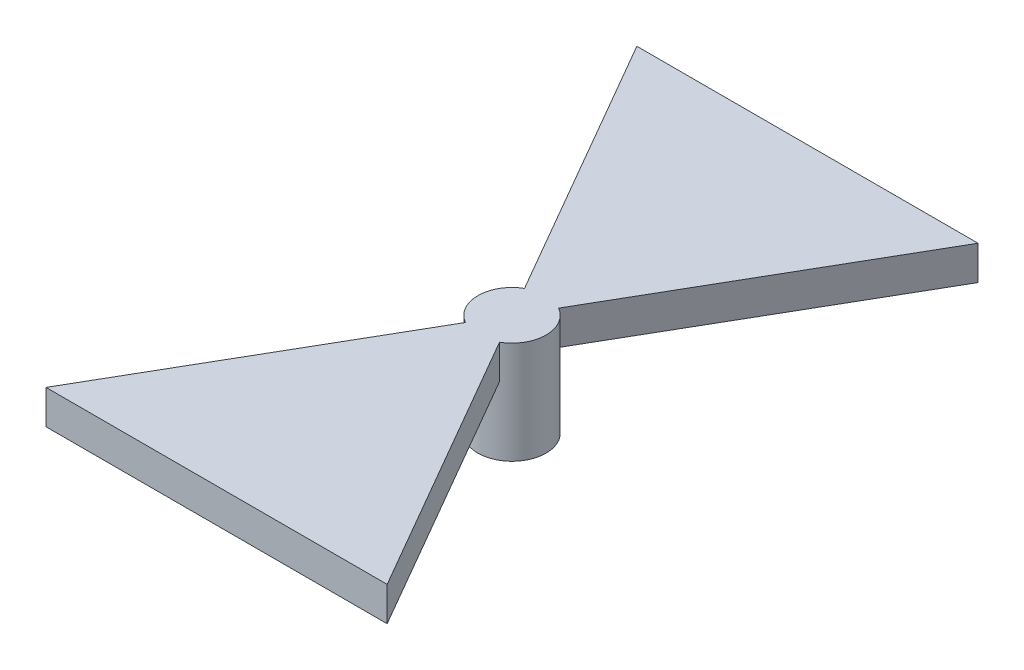
SolidWorks part; units mm, degrees
ref_plane "Plano frontal" through (0, 0, 0) normal (0, 0, 1) x (1, 0, 0)
ref_plane "Plano superior" through (0, 0, 0) normal (0, 1, 0) x (1, 0, 0)
ref_plane "Plano direito" through (0, 0, 0) normal (1, 0, 0) x (0, 0, -1)
sketch "Esboço1" plane through (0, 0, 0) normal (0, 1, 0) x (1, 0, 0)
  circle A0 centre (0, 0) radius 1
  circle A1 centre (0, 0) radius 2
  dimension "D1" = 2
  dimension "D2" = 4
extrude "Ressalto-extrusão1" add sketch "Esboço1" along normal blind 4
sketch "Esboço2" plane through (0, 4, 0) normal (0, 1, 0) x (1, 0, 0)
  line L0 (0, 0) -> (-10, 17.3205)
  line L1 (-10, 17.3205) -> (10, 17.3205)
  line L2 (10, 17.3205) -> (0, 0)
  line L3 (0, 0) -> (-10, -17.3205)
  line L4 (-10, -17.3205) -> (10, -17.3205)
  line L5 (10, -17.3205) -> (0, 0)
  circle A0 centre (0, 0) radius 2
  circle M7 centre (0, 0) radius 2
  dimension "D7" = 4
  dimension "D1" = 60
  dimension "D2" = 60
  dimension "D3" = 20
  dimension "D4" = 20
  dimension "D5" = 60
  dimension "D6" = 60
extrude "Ressalto-extrusão2" add sketch "Esboço2" along normal blind 2 contours L2 L1 L0 M7 | L4 L5 L3 M7 | A0
